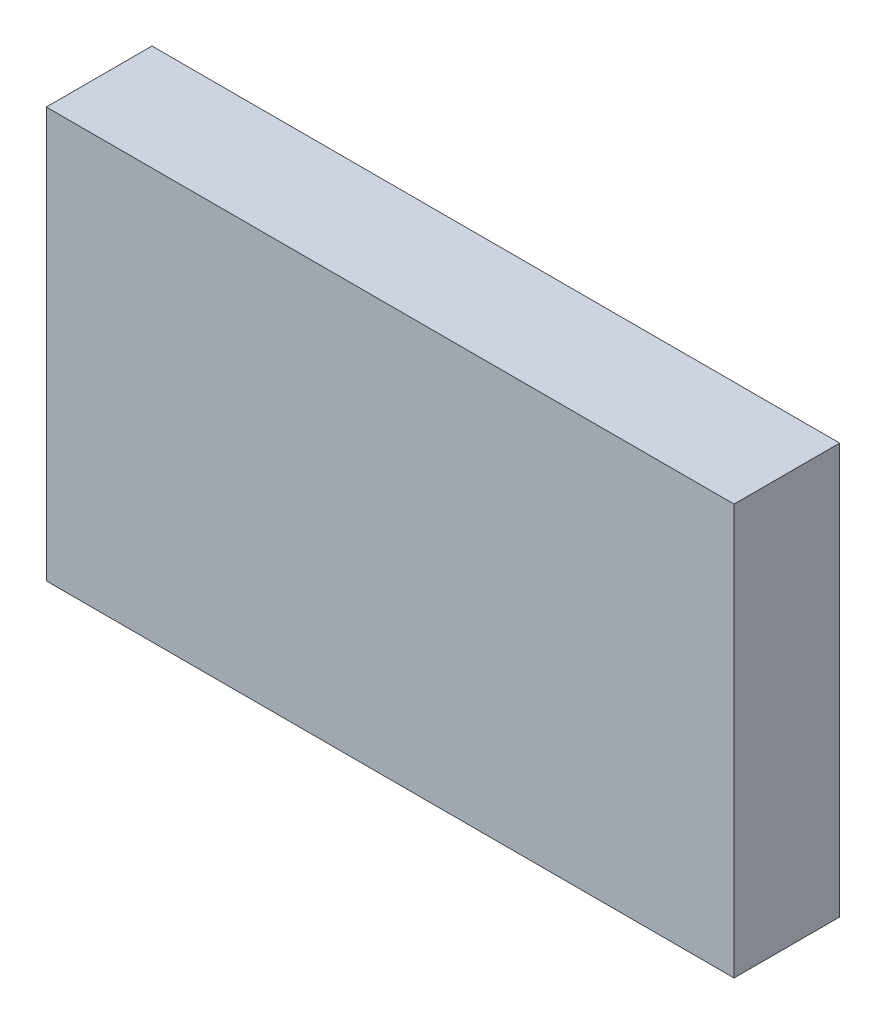
SolidWorks part; units mm, degrees
material "Silicon Rubber"
ref_plane "Front Plane" through (0, 0, 0) normal (0, 0, 1) x (1, 0, 0)
ref_plane "Top Plane" through (0, 0, 0) normal (0, 1, 0) x (1, 0, 0)
ref_plane "Right Plane" through (0, 0, 0) normal (1, 0, 0) x (0, 0, -1)
sketch "Sketch1" plane through (0, 0, 0) normal (0, 0, 1) x (1, 0, 0)
  line L1 (-15.5, 9.25) -> (15.5, 9.25)
  line L2 (-15.5, 9.25) -> (-15.5, -9.25)
  line L3 (-15.5, -9.25) -> (15.5, -9.25)
  line L4 (15.5, 9.25) -> (15.5, -9.25)
  line L5 (-15.5, 9.25) -> (15.5, -9.25) construction
  line L6 (-15.5, -9.25) -> (15.5, 9.25) construction
  point P0 (0, 0)
  dimension "D1" = 31
  dimension "D2" = 18.5
extrude "Boss-Extrude1" add sketch "Sketch1" along normal blind 4.7625
